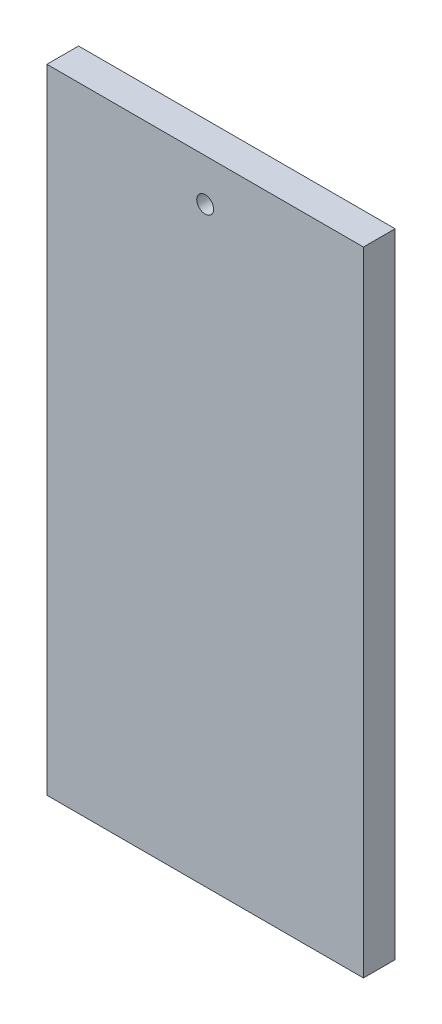
SolidWorks part; units mm, degrees
ref_plane "Front Plane" through (0, 0, 0) normal (0, 0, 1) x (1, 0, 0)
ref_plane "Top Plane" through (0, 0, 0) normal (0, 1, 0) x (1, 0, 0)
ref_plane "Right Plane" through (0, 0, 0) normal (1, 0, 0) x (0, 0, -1)
sketch "Sketch1" plane through (0, 0, 0) normal (0, 0, 1) x (1, 0, 0)
  line L1 (75, -150) -> (-75, -150)
  line L2 (75, -150) -> (75, 150)
  line L3 (75, 150) -> (-75, 150)
  line L4 (-75, -150) -> (-75, 150)
  line L5 (75, -150) -> (-75, 150) construction
  line L6 (75, 150) -> (-75, -150) construction
  circle A0 centre (0, 130) radius 4
  point P0 (0, 0)
  dimension "D3" = 8
  dimension "D1" = 300
  dimension "D2" = 150
  dimension "D4" = 20
extrude "Boss-Extrude1" add sketch "Sketch1" along normal blind 15
